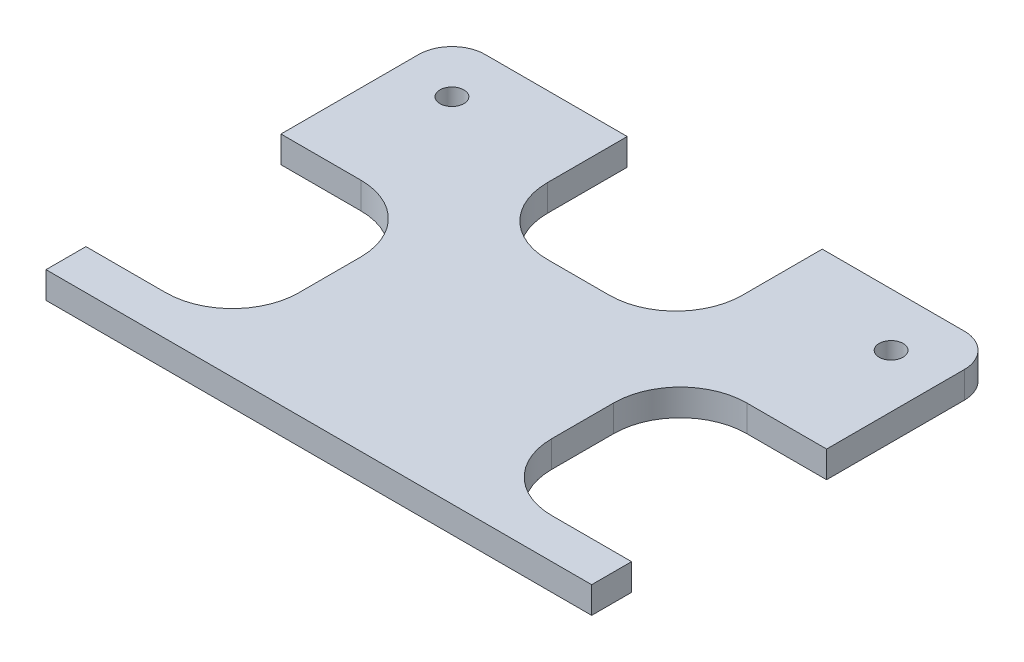
SolidWorks part; units mm, degrees
ref_plane "Front Plane" through (0, 0, 0) normal (0, 0, 1) x (1, 0, 0)
ref_plane "Top Plane" through (0, 0, 0) normal (0, 1, 0) x (1, 0, 0)
ref_plane "Right Plane" through (0, 0, 0) normal (1, 0, 0) x (0, 0, -1)
sketch "Sketch1" plane through (0, 0, 0) normal (0, 1, 0) x (1, 0, 0)
  line L0 (8, 53) -> (74, 53) construction
  line L1 (0, 0) -> (82, 0)
  line L2 (0, 0) -> (0, 56)
  line L3 (5, 61) -> (77, 61)
  line L4 (82, 0) -> (82, 56)
  line L5 (41, 0) -> (41, 53) construction
  circle A0 centre (8, 53) radius 1.8
  circle A1 centre (74, 53) radius 1.8
  arc A2 (82, 56) -> (77, 61) centre (77, 56) ccw
  arc A3 (0, 56) -> (5, 61) centre (5, 56) cw
  point P12 (41, 53)
  point P18 (0, 61)
  dimension "D3" = 66
  dimension "D5" = 3.6
  dimension "D6" = 5
  dimension "D1" = 82
  dimension "D2" = 61
  dimension "D4" = 8
extrude "Boss-Extrude1" add sketch "Sketch1" along normal blind 4
sketch "Sketch2" plane through (0, 4, 0) normal (0, 1, 0) x (1, 0, 0)
  line L0 (77, 61) -> (5, 61) construction
  line L1 (26.3465, 61) -> (55.6535, 61)
  line L2 (26.3465, 61) -> (26.3465, 39)
  line L3 (26.3465, 39) -> (55.6535, 39)
  line L4 (55.6535, 61) -> (55.6535, 39)
  line L5 (82, 0) -> (82, 56) construction
  line L6 (82, 35.307) -> (60, 35.307)
  line L7 (82, 35.307) -> (82, 6)
  line L8 (82, 6) -> (60, 6)
  line L9 (60, 35.307) -> (60, 6)
  line L10 (0, 56) -> (0, 0) construction
  line L11 (0, 35.307) -> (22, 35.307)
  line L12 (0, 35.307) -> (0, 6)
  line L13 (0, 6) -> (22, 6)
  line L14 (22, 35.307) -> (22, 6)
  line L15 (41, 0) -> (41, 39) construction
  line L16 (0, 0) -> (82, 0) construction
  dimension "D1" = 22
  dimension "D2" = 6
extrude "Cut-Extrude1" cut sketch "Sketch2" against normal through all
fillet "Fillet1" radius 10 6 edges at (55.6535, 2, -39) (26.3465, 2, -39) (60, 2, -6) (60, 2, -35.307) (22, 2, -6) (22, 2, -35.307)
